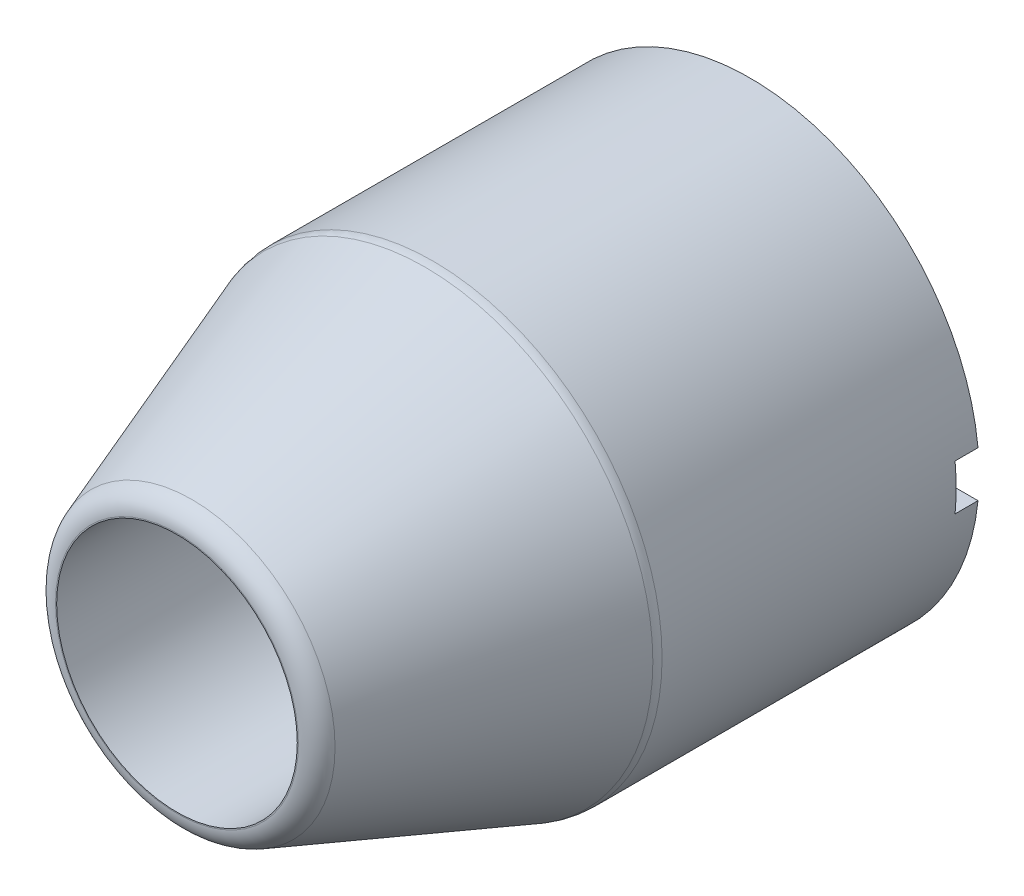
SolidWorks part; units mm, degrees
ref_plane "Front Plane" through (0, 0, 0) normal (0, 0, 1) x (1, 0, 0)
ref_plane "Top Plane" through (0, 0, 0) normal (0, 1, 0) x (1, 0, 0)
ref_plane "Right Plane" through (0, 0, 0) normal (1, 0, 0) x (0, 0, -1)
sketch "Sketch1" plane through (0, 0, 0) normal (0, 0, 1) x (1, 0, 0)
  circle A0 centre (0, 0) radius 10
  dimension "D1" = 20
extrude "Boss-Extrude1" add sketch "Sketch1" along normal blind 25
sketch "Sketch2" plane through (0, 0, 25) normal (0, 0, 1) x (1, 0, 0)
  circle A0 centre (0, 0) radius 2
  dimension "D1" = 4
extrude "Cut-Extrude1" cut sketch "Sketch2" against normal through all
sketch "Sketch3" plane through (0, 0, 25) normal (0, 0, 1) x (1, 0, 0)
  circle A0 centre (0, 0) radius 5.25
  dimension "D1" = 10.5
extrude "Cut-Extrude2" cut sketch "Sketch3" against normal blind 8
chamfer "Chamfer1" distance 4 angle 70 1 edges at (10, 0, 25)
chamfer "Chamfer2" distance 2 angle 45 1 edges at (2, 0, 0)
fillet "Fillet1" radius 1 2 edges at (6, 0, 25) (10, 0, 14.0101)
sketch "Sketch4" plane through (0, 0, 0) normal (0, 0, -1) x (-1, 0, 0)
  line L1 (-11.2329, 1) -> (11.2329, 1)
  line L2 (-11.2329, 1) -> (-11.2329, -1)
  line L3 (-11.2329, -1) -> (11.2329, -1)
  line L4 (11.2329, 1) -> (11.2329, -1)
  line L5 (-11.2329, 1) -> (11.2329, -1) construction
  line L6 (-11.2329, -1) -> (11.2329, 1) construction
  point P0 (0, 0)
  dimension "D1" = 2
extrude "Cut-Extrude3" cut sketch "Sketch4" against normal blind 1
